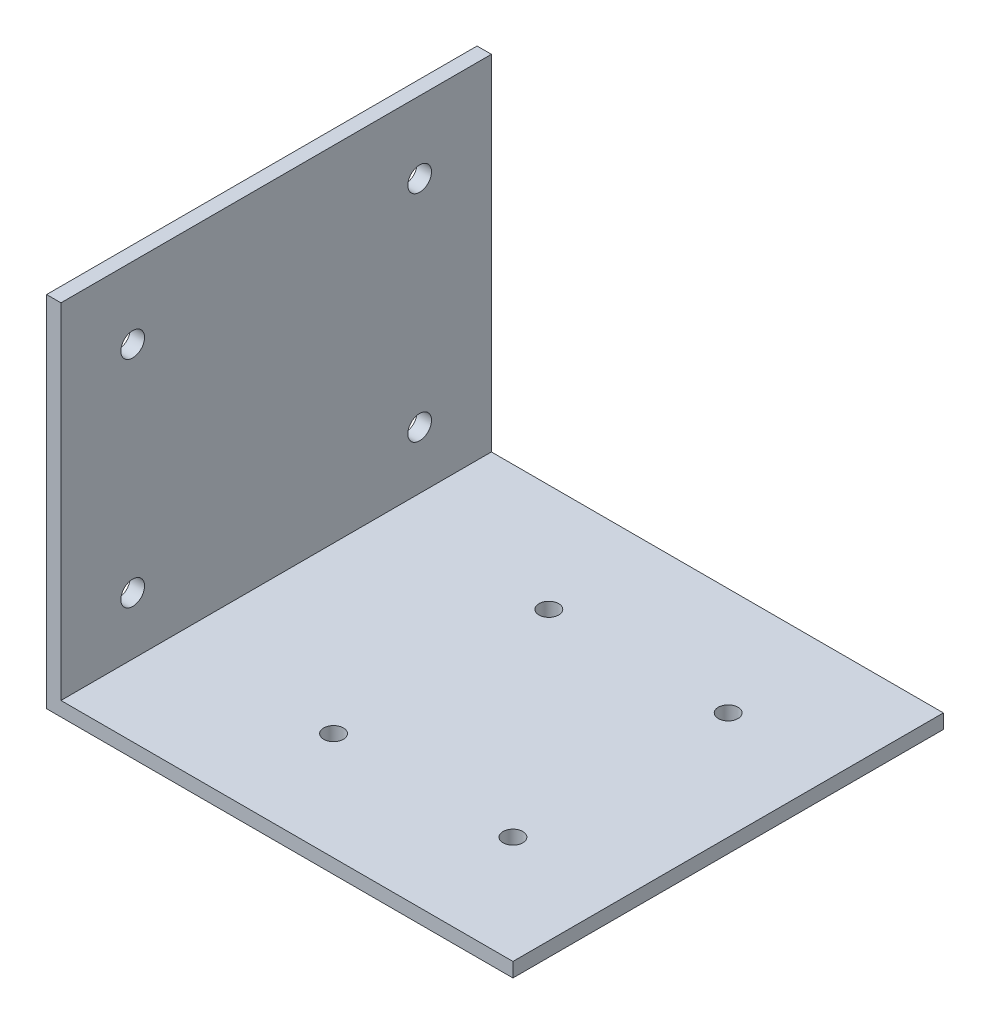
SolidWorks part; units mm, degrees
material "6061-T6 (SS)"
ref_plane "Front Plane" through (0, 0, 0) normal (0, 0, 1) x (1, 0, 0)
ref_plane "Top Plane" through (0, 0, 0) normal (0, 1, 0) x (1, 0, 0)
ref_plane "Right Plane" through (0, 0, 0) normal (1, 0, 0) x (0, 0, -1)
sketch "Sketch2" plane through (0, 0, 0) normal (0, 0, 1) x (1, 0, 0)
  line L0 (0, 0) -> (0, 100)
  line L1 (0, 100) -> (4, 100)
  line L2 (4, 100) -> (4, 4)
  line L3 (4, 4) -> (130, 4)
  line L4 (130, 4) -> (130, 0)
  line L5 (130, 0) -> (0, 0)
  dimension "D1" = 100
  dimension "D2" = 4
  dimension "D3" = 4
  dimension "D4" = 130
extrude "Boss-Extrude1" add sketch "Sketch2" along normal blind 120
sketch "Sketch4" plane through (4, 0, 0) normal (1, 0, 0) x (0, 0, -1)
  line L0 (0, 4) -> (0, 100) construction
  line L1 (-120, 100) -> (0, 100) construction
  circle A0 centre (-100, 80) radius 3.3
  circle A1 centre (-20, 80) radius 3.3
  circle A2 centre (-20, 20) radius 3.3
  circle A3 centre (-100, 20) radius 3.3
  dimension "D1" = 6.6
  dimension "D2" = 60
  dimension "D3" = 80
  dimension "D4" = 20
  dimension "D5" = 20
extrude "Cut-Extrude1" cut sketch "Sketch4" against normal through all
sketch "Sketch5" plane through (0, 4, 0) normal (0, 1, 0) x (1, 0, 0)
  line L0 (0, -120) -> (0, 0) construction
  line L1 (130, -120) -> (4, -120) construction
  circle A0 centre (100, -30) radius 2.75
  circle A1 centre (50, -30) radius 2.75
  circle A2 centre (50, -90) radius 2.75
  circle A3 centre (100, -90) radius 2.75
  dimension "D1" = 5.5
  dimension "D2" = 50
  dimension "D3" = 60
  dimension "D4" = 50
  dimension "D5" = 30
extrude "Cut-Extrude2" cut sketch "Sketch5" against normal through all
